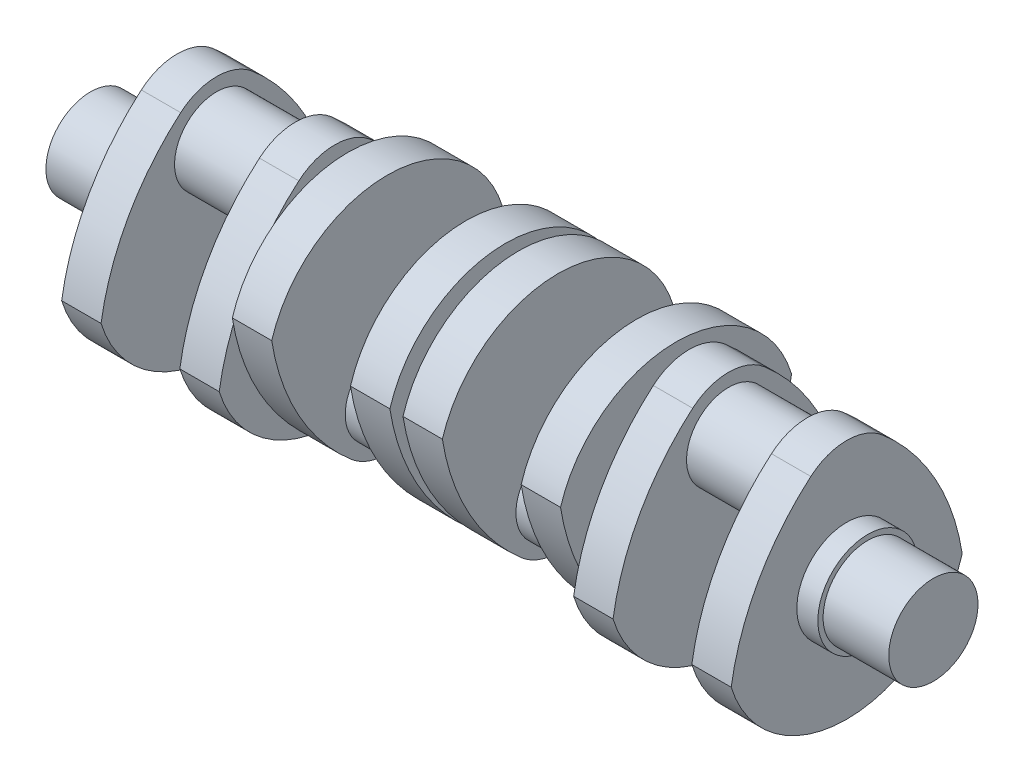
SolidWorks part; units mm, degrees
ref_plane "Front Plane" through (0, 0, 0) normal (0, 0, 1) x (1, 0, 0)
ref_plane "Top Plane" through (0, 0, 0) normal (0, 1, 0) x (1, 0, 0)
ref_plane "Right Plane" through (0, 0, 0) normal (1, 0, 0) x (0, 0, -1)
sketch "Sketch1" plane through (0, 0, 0) normal (1, 0, 0) x (0, 0, -1)
  circle A0 centre (0, 0) radius 17
  circle A1 centre (0, 0) radius 19
  dimension "D1" = 34
  dimension "D2" = 38
extrude "Boss-Extrude3" add sketch "Sketch1" against normal blind 25 contours A0
sketch "Sketch3" plane through (0, 0, 0) normal (1, 0, 0) x (0, 0, -1)
  circle A0 centre (0, 0) radius 19
  dimension "D1" = 38
extrude "Boss-Extrude4" add sketch "Sketch3" along normal blind 8
sketch "Sketch4" plane through (8, 0, 0) normal (1, 0, 0) x (0, 0, -1)
  arc A0 (-13.6681, 40.9431) -> (13.6681, 40.9431) centre (0, 25) cw
  arc A1 (-44, -13.4164) -> (44, -13.4164) centre (0, 0) ccw
  arc A2 (-13.6681, 40.9431) -> (-44, -13.4164) centre (44.9095, -27.3845) ccw
  arc A3 (13.6681, 40.9431) -> (44, -13.4164) centre (-44.9095, -27.3845) cw
  point P8 (0, 0)
  point P10 (0, 0)
  dimension "D1" = 25
  dimension "D3" = 46
  dimension "D4" = 21
  dimension "D5" = 90
  dimension "D6" = 90
  dimension "D2" = 88
extrude "Boss-Extrude5" add sketch "Sketch4" along normal blind 15
sketch "Sketch5" plane through (23, 0, 0) normal (1, 0, 0) x (0, 0, -1)
  circle A0 centre (0, 25) radius 16
  dimension "D1" = 32
extrude "Boss-Extrude6" add sketch "Sketch5" along normal blind 15
mirror "Mirror1" about plane through (38, 25, 0) normal (1, 0, 0) of "Boss-Extrude6", "Boss-Extrude5"
sketch "Sketch6" plane through (68, 0, 0) normal (1, 0, 0) x (0, 0, -1)
  circle A0 centre (0, 0) radius 17
  dimension "D1" = 34
extrude "Boss-Extrude7" add sketch "Sketch6" along normal blind 5
sketch "Sketch7" plane through (73, 0, 0) normal (1, 0, 0) x (0, 0, -1)
  circle A0 centre (0, 0) radius 17 construction
  arc A8 (-13.6681, -40.9431) -> (13.6681, -40.9431) centre (0, -25) ccw
  arc A9 (-44, 13.4164) -> (-13.6681, -40.9431) centre (44.9095, 27.3845) ccw
  arc A10 (44, 13.4164) -> (-44, 13.4164) centre (0, 0) ccw
  arc A11 (13.6681, -40.9431) -> (44, 13.4164) centre (-44.9095, 27.3845) ccw
  dimension "D1" = 21
  dimension "D2" = 90
  dimension "D3" = 46
  dimension "D4" = 13.6681
  dimension "D5" = 44
  dimension "D6" = 44.9095
  dimension "D7" = 13.6681
extrude "Boss-Extrude8" add sketch "Sketch7" along normal blind 15
sketch "Sketch8" plane through (88, 0, 0) normal (1, 0, 0) x (0, 0, -1)
  circle A0 centre (0, -25) radius 16
  dimension "D1" = 32
  dimension "D2" = 25
extrude "Boss-Extrude9" add sketch "Sketch8" along normal blind 30
sketch "Sketch9" plane through (118, 0, 0) normal (1, 0, 0) x (0, 0, -1)
  arc A4 (-13.6681, -40.9431) -> (13.6681, -40.9431) centre (0, -25) ccw
  arc A5 (13.6681, -40.9431) -> (44, 13.4164) centre (-44.9095, 27.3845) ccw
  arc A6 (44, 13.4164) -> (-44, 13.4164) centre (0, 0) ccw
  arc A7 (-44, 13.4164) -> (-13.6681, -40.9431) centre (44.9095, 27.3845) ccw
  arc A8 (-13.6681, -40.9431) -> (13.6681, -40.9431) centre (0, -25) ccw
  arc A9 (13.6681, -40.9431) -> (44, 13.4164) centre (-44.9095, 27.3845) ccw
  arc A10 (44, 13.4164) -> (-44, 13.4164) centre (0, 0) ccw
  arc A11 (-44, 13.4164) -> (-13.6681, -40.9431) centre (44.9095, 27.3845) ccw
  dimension "D1" = 0
extrude "Boss-Extrude10" add sketch "Sketch9" along normal blind 15
sketch "Sketch10" plane through (133, 0, 0) normal (1, 0, 0) x (0, 0, -1)
  circle A0 centre (0, 0) radius 17
  dimension "D1" = 34
extrude "Boss-Extrude11" add sketch "Sketch10" along normal blind 2.5
mirror "Mirror2" about plane through (135.5, 0, 0) normal (1, 0, 0) of bodies 112
